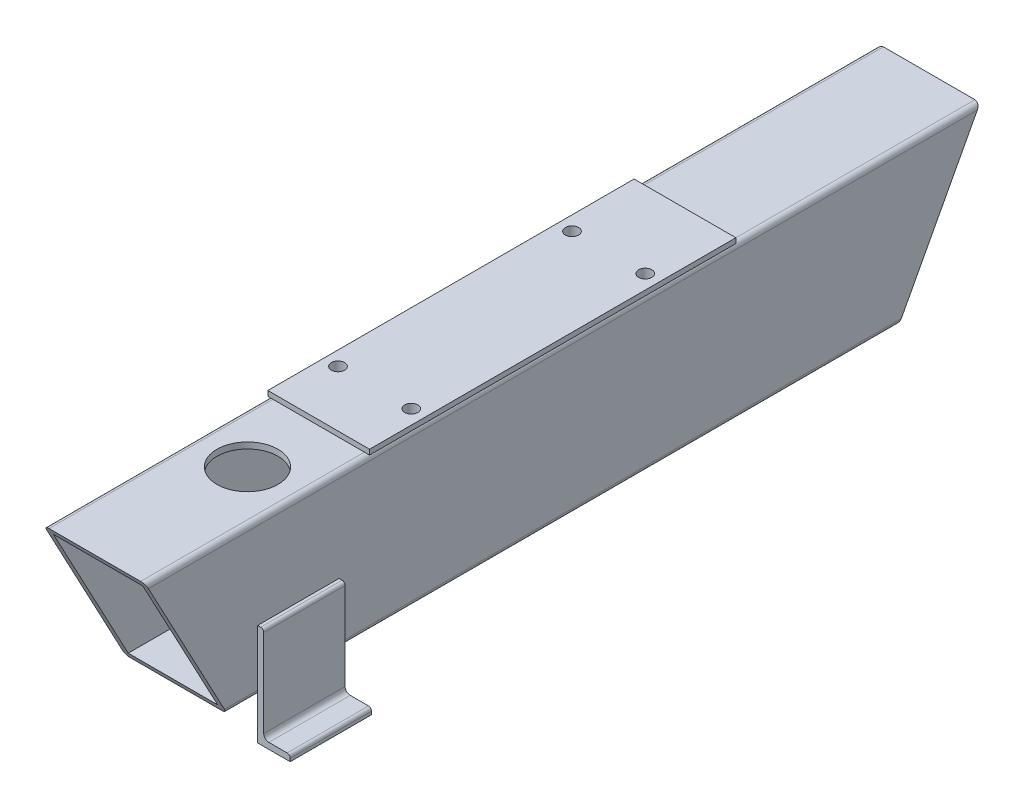
SolidWorks part; units mm, degrees
material "Structural Steel"
ref_plane "Piano frontale" through (0, 0, 0) normal (0, 0, 1) x (1, 0, 0)
ref_plane "Piano superiore" through (0, 0, 0) normal (0, 1, 0) x (1, 0, 0)
ref_plane "Piano destro" through (0, 0, 0) normal (1, 0, 0) x (0, 0, -1)
sketch "Schizzo1" plane through (0, 0, 0) normal (0, 0, 1) x (1, 0, 0)
  line L1 (5, 0) -> (95, 0)
  line L2 (0, 5) -> (0, 145)
  line L3 (5, 150) -> (95, 150)
  line L4 (100, 5) -> (100, 145)
  arc A0 (0, 145) -> (5, 150) centre (5, 145) cw
  arc A1 (95, 150) -> (100, 145) centre (95, 145) cw
  arc A2 (95, 0) -> (100, 5) centre (95, 5) ccw
  arc A3 (5, 0) -> (0, 5) centre (5, 5) cw
  point P7 (0, 150)
  point P12 (100, 0)
  point P15 (0, 0)
  dimension "D3" = 5
  dimension "D1" = 100
  dimension "D2" = 150
extrude "Estrusione-Sottile1" add sketch "Schizzo1" along normal blind 1000 thin
sketch "Schizzo2" plane through (100, 0, 0) normal (1, 0, 0) x (0, 0, -1)
  line L0 (-920, 178.0473) -> (-920, -33.1937) construction
  line L1 (-1000, 5) -> (-1000, 145) construction
  line L2 (-920, 0) -> (-1000, 150)
  line L3 (-1000, 150) -> (-1000, 0)
  line L4 (-1000, 0) -> (-920, 0)
  dimension "D1" = 80
extrude "Estrusione1" cut sketch "Schizzo2" against normal through all
sketch "Schizzo3" plane through (100, 0, 0) normal (1, 0, 0) x (0, 0, -1)
  line L0 (-260, 227.1862) -> (-260, -99.833) construction
  line L1 (-180, 227.1862) -> (-180, -97.5683) construction
  line L2 (-180, 150) -> (-260, 0)
  line L4 (-260, 0) -> (0, 0)
  line L5 (0, 0) -> (0, 150)
  line L6 (-1000, 150) -> (0, 150) construction
  line L7 (-180, 150) -> (0, 150)
  dimension "D1" = 660
  dimension "D2" = 80
extrude "Estrusione2" cut sketch "Schizzo3" against normal through all
sketch "Schizzo4" plane through (0, 0, 0) normal (0, -1, 0) x (1, 0, 0)
  line L0 (50, 920) -> (50, 716.89) construction
  line L1 (5, 920) -> (95, 920) construction
  circle A0 centre (50, 850) radius 30
  dimension "D1" = 60
  dimension "D2" = 70
extrude "Estrusione3" cut sketch "Schizzo4" against normal through all
sketch "Schizzo7" plane through (0, 150, 0) normal (0, 1, 0) x (1, 0, 0)
  line L0 (0, -997.3333) -> (0, -182.6667) construction
  line L1 (0, -420) -> (100, -420)
  line L2 (0, -420) -> (0, -780)
  line L3 (0, -780) -> (100, -780)
  line L4 (100, -420) -> (100, -780)
  line L5 (100, -997.3333) -> (100, -182.6667) construction
  circle A0 centre (50, -850) radius 30 construction
  dimension "D3" = 70
  dimension "D1" = 100
  dimension "D2" = 360
extrude "Estrusione6" add sketch "Schizzo7" along normal blind 5
sketch "Schizzo6" plane through (0, 0, 0) normal (0, -1, 0) x (1, 0, 0)
  line L0 (50, -150) -> (50, 49850) construction
  circle A0 centre (14, 725) radius 6.5
  circle A1 centre (14, 495) radius 6.5
  circle A2 centre (50, 850) radius 30 construction
  circle A3 centre (86, 495) radius 6.5
  circle A4 centre (86, 725) radius 6.5
  dimension "D1" = 13
  dimension "D2" = 13
  dimension "D3" = 125
  dimension "D4" = 230
  dimension "D5" = 36
  dimension "D6" = 36
extrude "Estrusione5" cut sketch "Schizzo6" against normal through all
ref_plane "Piano1" through (0, 0, 850) normal (0, 0, 1) x (1, 0, 0)
sketch "Schizzo9" plane through (0, 0, 850) normal (0, 0, 1) x (1, 0, 0)
  line L0 (100, 60) -> (100, -40)
  line L1 (100, 5) -> (100, 145) construction
  line L2 (100, -40) -> (132, -40)
  line L3 (5, 0) -> (95, 0) construction
  line L4 (132, -40) -> (132, -37)
  line L5 (129, -34) -> (111, -34)
  line L6 (106, -29) -> (106, 57)
  line L7 (103, 60) -> (100, 60)
  arc A0 (111, -34) -> (106, -29) centre (111, -29) cw
  arc A1 (132, -37) -> (129, -34) centre (129, -37) ccw
  arc A2 (106, 57) -> (103, 60) centre (103, 57) ccw
  dimension "D6" = 5
  dimension "D7" = 3
  dimension "D1" = 32
  dimension "D2" = 40
  dimension "D3" = 100
  dimension "D4" = 6
  dimension "D5" = 6
extrude "Estrusione7" add sketch "Schizzo9" along normal blind 40 and the other way blind 40
